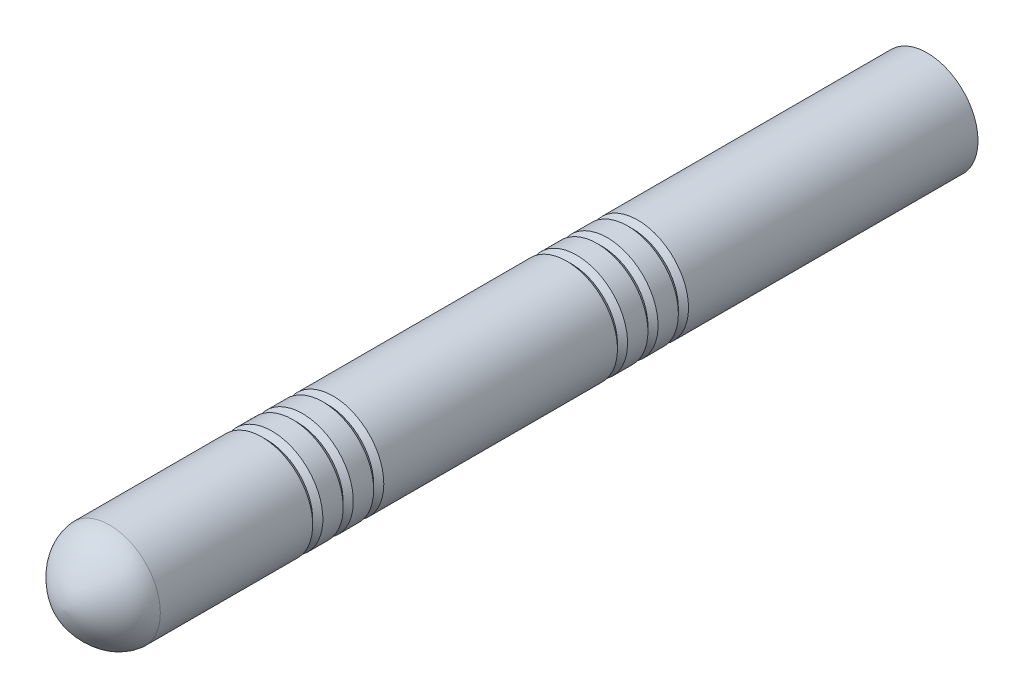
SolidWorks part; units mm, degrees
ref_plane "前视基准面" through (0, 0, 0) normal (0, 0, 1) x (1, 0, 0)
ref_plane "上视基准面" through (0, 0, 0) normal (0, 1, 0) x (1, 0, 0)
ref_plane "右视基准面" through (0, 0, 0) normal (1, 0, 0) x (0, 0, -1)
sketch "草图1" plane through (0, 0, 0) normal (0, 0, 1) x (1, 0, 0)
  circle A0 centre (0, 0) radius 5
  dimension "D1" = 10
extrude "凸台-拉伸1" add sketch "草图1" along normal blind 80.5
sketch "草图2" plane through (0, 0, 0) normal (1, 0, 0) x (0, 0, -1)
  line L0 (-95.7456, 0) -> (-68.6048, 0) construction
  line L1 (-28.5, 5) -> (-29, 4.5)
  line L2 (0, 5) -> (-80.5, 5) construction
  line L3 (-29, 3.6495) -> (-29, 6.2996) construction
  line L4 (-29.5, 5) -> (-29, 4.5)
  line L5 (-28.5, 5) -> (-29.5, 5)
  line L6 (0, -5) -> (0, 5) construction
  point P12 (-29, 5)
  dimension "D1" = 29
  dimension "D2" = 0.5
  dimension "D3" = 90
revolve "切除-旋转1" cut sketch "草图2" angle 360 about L0
sketch "草图4" plane through (0, 0, 0) normal (1, 0, 0) x (0, 0, -1)
  line L0 (-31.5, 5) -> (-32, 4.5)
  line L1 (-32.5, 5) -> (-32, 4.5)
  line L2 (-31.5, 5) -> (-32.5, 5)
  line L3 (0, 5) -> (-28.5, 5) construction
  line L4 (-29, 4.5) -> (-29, -4.5) construction
  line L5 (-34.5, 5) -> (-35, 4.5)
  line L6 (-35.5, 5) -> (-35, 4.5)
  line L7 (-34.5, 5) -> (-35.5, 5)
  line L8 (1.9726, 0) -> (-7.0086, 0) construction
  point P3 (-32, 5)
  point P11 (-35, 5)
  dimension "D1" = 0.5
  dimension "D2" = 90
  dimension "D3" = 3
  dimension "D4" = 0.5
  dimension "D5" = 90
  dimension "D6" = 3
  dimension "D7" = 0
revolve "切除-旋转2" cut sketch "草图4" angle 360 about L8
pattern_linear "阵列(线性)1" count 2 spacing 30 along (0, 0, 1) of "切除-旋转1", "切除-旋转2"
sketch "草图5" plane through (0, 0, 0) normal (1, 0, 0) x (0, 0, -1)
  line L0 (-80.5, 5) -> (-80.5, -5) construction
  line L1 (-65.5, 5) -> (-80.5, 5) construction
  line L2 (-80.5, 0) -> (-85, 0)
  line L4 (-87.7828, 0) -> (-81.7836, 0) construction
  line L5 (-80.5, 5) -> (-80.5, 0)
  spline S0 degree 3 poles (-80.5, 5) (-81.8089, 4.8875) (-83.7607, 3.3186) (-84.9084, 1.1787) (-85, 0) knots 0 0 0 0 0.522009 1 1 1 1
  point P0 (-80.5, 0)
  point P1 (-76, 5)
  point P4 (-84.5365, 1.6915)
  point P7 (-83.6275, 3.094)
  point P8 (-82.0952, 4.4704)
  dimension "D2" = 85
revolve "旋转2" add sketch "草图5" angle 360 about L4
hole_wizard "M8 螺纹孔1" positions "草图7" profile "草图8" tap size "M8" standard "GB"
sketch "草图7" plane through (0, 0, 0) normal (0, 0, -1) x (-1, 0, 0)
  point P0 (0, 0)
sketch "草图8" plane through (0, 0, 0) normal (1, 0, 0) x (0, 1, 0)
  line L0 (0, 0) -> (0, 69.033)
  line L1 (0, 69.033) -> (3.4, 67.07)
  line L2 (3.4, 67.07) -> (3.4, 0)
  line L5 (3.4, 0) -> (0, 0)
  line L10 (0, 69.033) -> (-3.4, 67.07) construction
  line L11 (0, -6.35) -> (0, 107.95) construction
  dimension "螺纹孔钻头直径" = 6.8
  dimension "螺纹孔钻头深度" = 67.07
  dimension "导头角度" = 120
cosmetic thread "孔螺蚊线1" parameters "D1"=20, "D2"=8
